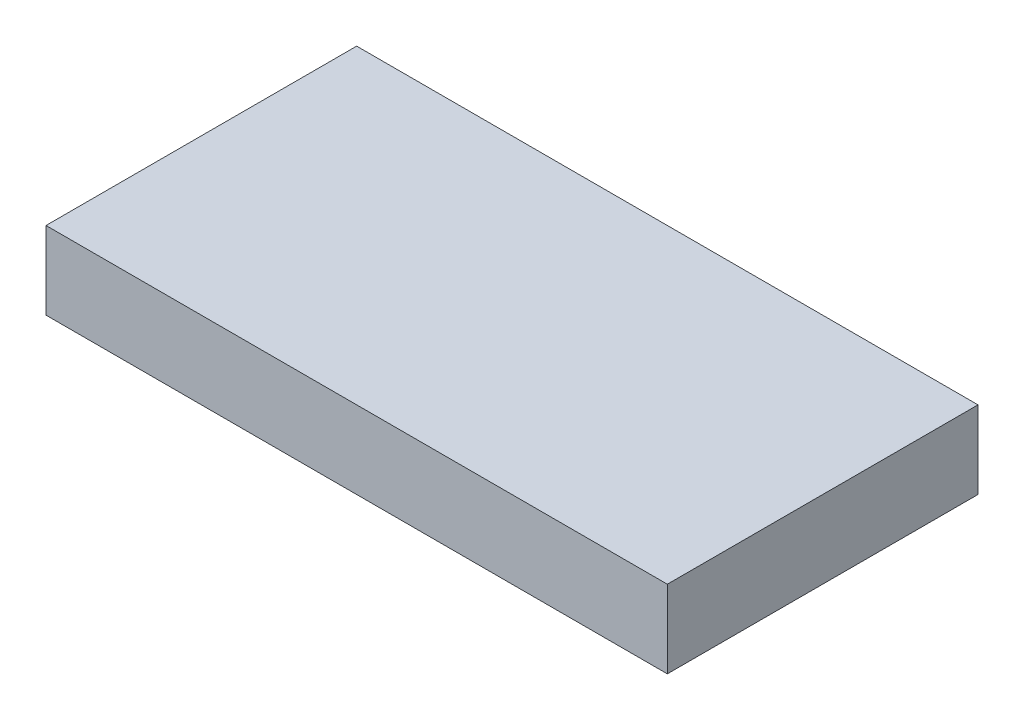
SolidWorks part; units mm, degrees
ref_plane "Front Plane" through (0, 0, 0) normal (0, 0, 1) x (1, 0, 0)
ref_plane "Top Plane" through (0, 0, 0) normal (0, 1, 0) x (1, 0, 0)
ref_plane "Right Plane" through (0, 0, 0) normal (1, 0, 0) x (0, 0, -1)
sketch "Sketch1" plane through (0, 0, 0) normal (0, 1, 0) x (1, 0, 0)
  line L1 (0, 0) -> (508, 0)
  line L2 (0, 0) -> (0, 254)
  line L3 (0, 254) -> (508, 254)
  line L4 (508, 0) -> (508, 254)
  dimension "D1" = 254
  dimension "D2" = 508
extrude "Boss-Extrude1" add sketch "Sketch1" along normal blind 63.5
